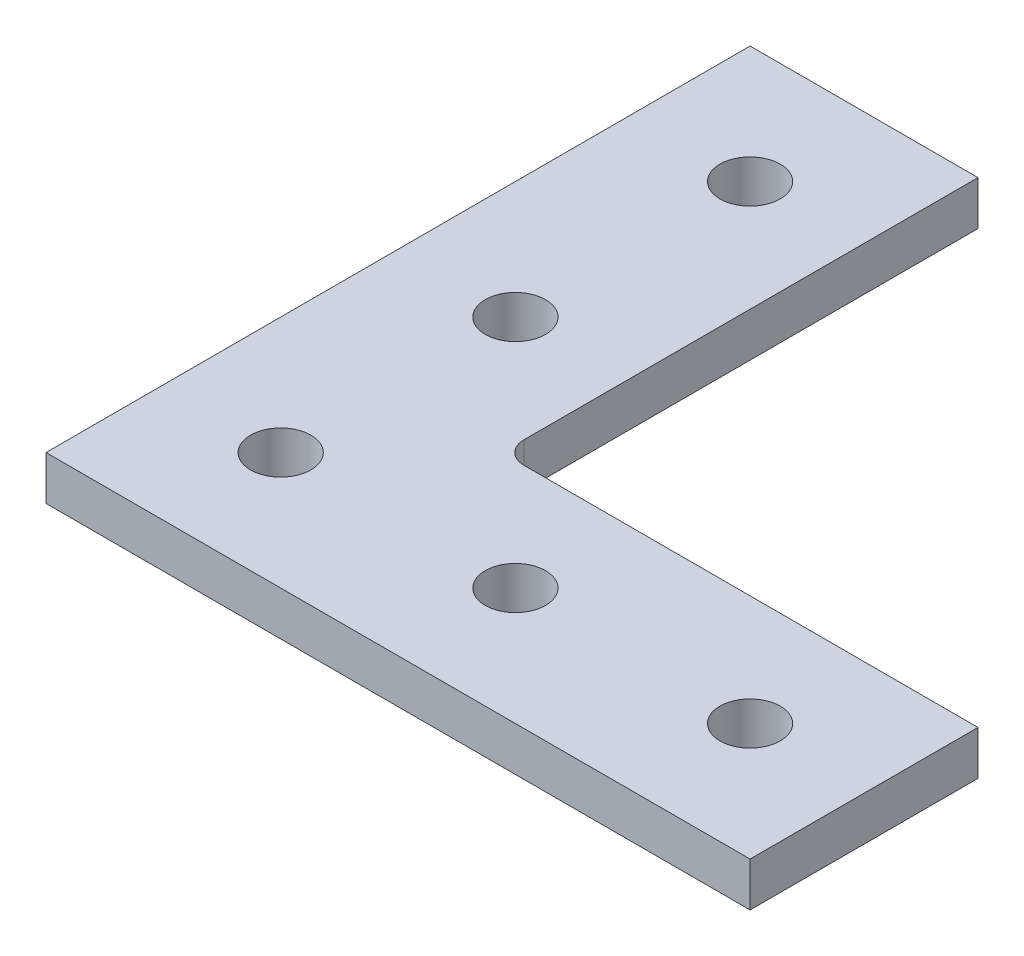
SolidWorks part; units mm, degrees
material "6105-T5 Aluminum"
ref_plane "Front Plane" through (0, 0, 0) normal (0, 0, 1) x (1, 0, 0)
ref_plane "Top Plane" through (0, 0, 0) normal (0, 1, 0) x (1, 0, 0)
ref_plane "Right Plane" through (0, 0, 0) normal (1, 0, 0) x (0, 0, -1)
sketch "Sketch1" plane through (0, 0, 0) normal (0, 1, 0) x (1, 0, 0)
  line L0 (24.667, 76.2) -> (24.667, 27.0482)
  line L1 (0, 76.2) -> (24.667, 76.2)
  line L2 (0, 0) -> (0, 76.2)
  line L3 (0, 0) -> (76.2, 0)
  line L4 (27.0482, 24.667) -> (76.2, 24.667)
  line L5 (76.2, 24.667) -> (76.2, 0)
  arc A0 (24.667, 27.0482) -> (27.0482, 24.667) centre (27.0482, 27.0482) ccw
  circle A1 centre (12.7, 63.5) radius 3.2639
  circle A2 centre (12.7, 38.1) radius 3.2639
  circle A3 centre (12.7, 12.7) radius 3.2639
  circle A4 centre (38.1, 12.7) radius 3.2639
  circle A5 centre (63.5, 12.7) radius 3.2639
extrude "Extrude1" add sketch "Sketch1" along normal blind 4.7752
